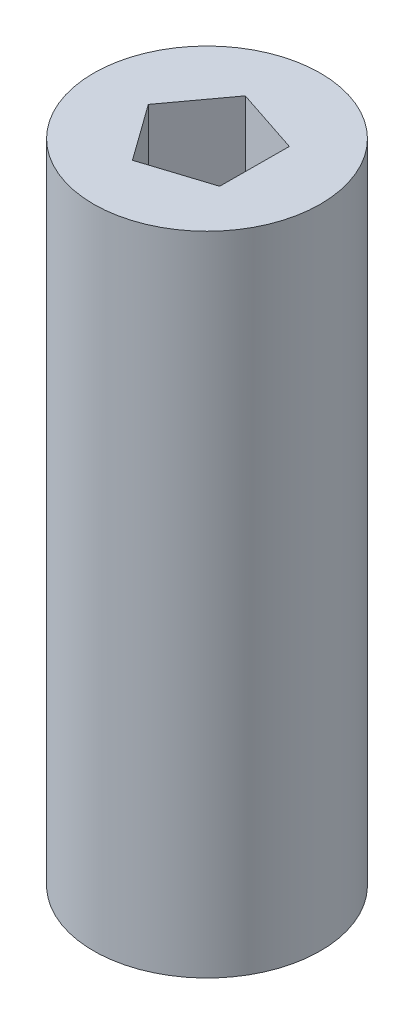
SolidWorks part; units mm, degrees
ref_plane "Front Plane" through (0, 0, 0) normal (0, 0, 1) x (1, 0, 0)
ref_plane "Top Plane" through (0, 0, 0) normal (0, 1, 0) x (1, 0, 0)
ref_plane "Right Plane" through (0, 0, 0) normal (1, 0, 0) x (0, 0, -1)
sketch "Sketch1" plane through (0, 0, 0) normal (0, 1, 0) x (1, 0, 0)
  line L0 (2.0951, -1.5397) -> (2.1117, 1.5168)
  line L1 (2.1117, 1.5168) -> (-0.79, 2.4771)
  line L2 (-0.79, 2.4771) -> (-2.6, 0.0141)
  line L3 (-2.6, 0.0141) -> (-0.8169, -2.4683)
  line L4 (-0.8169, -2.4683) -> (2.0951, -1.5397)
  circle A0 centre (0, 0) radius 5
  circle A1 centre (0, 0) radius 2.5 construction
  circle A2 centre (0, 0) radius 2.6
  dimension "D1" = 10
extrude "Boss-Extrude1" add sketch "Sketch1" along normal blind 8 contours A0 A2 | L0 A2 | L4 A2 | L3 A2 | L2 A2 | L1 A2
sketch "Sketch2" plane through (0, 0, 0) normal (0, -1, 0) x (1, 0, 0)
  circle A0 centre (0, 0) radius 5
  circle A1 centre (0, 0) radius 5 construction
  circle A2 centre (0, 0) radius 2.175
  dimension "D1" = 4.35
extrude "Boss-Extrude2" add sketch "Sketch2" along normal blind 6
sketch "Sketch3" plane through (0, -6, 0) normal (0, -1, 0) x (1, 0, 0)
  circle A0 centre (0, 0) radius 5
  circle A1 centre (0, 0) radius 5 construction
extrude "Boss-Extrude3" add sketch "Sketch3" along normal blind 1.5
sketch "Sketch4" plane through (0, -7.5, 0) normal (0, -1, 0) x (1, 0, 0)
  line L0 (-1.7471, 2.5) -> (1.7471, 2.5)
  circle A0 centre (0, 0) radius 3.05
  circle A1 centre (0, 0) radius 5
  circle A2 centre (0, 0) radius 5 construction
  circle M4 centre (0, 0) radius 5
  dimension "D1" = 6.1
  dimension "D2" = 2.5
extrude "Boss-Extrude4" add sketch "Sketch4" along normal blind 13 contours L0 A0 | A0 M4
